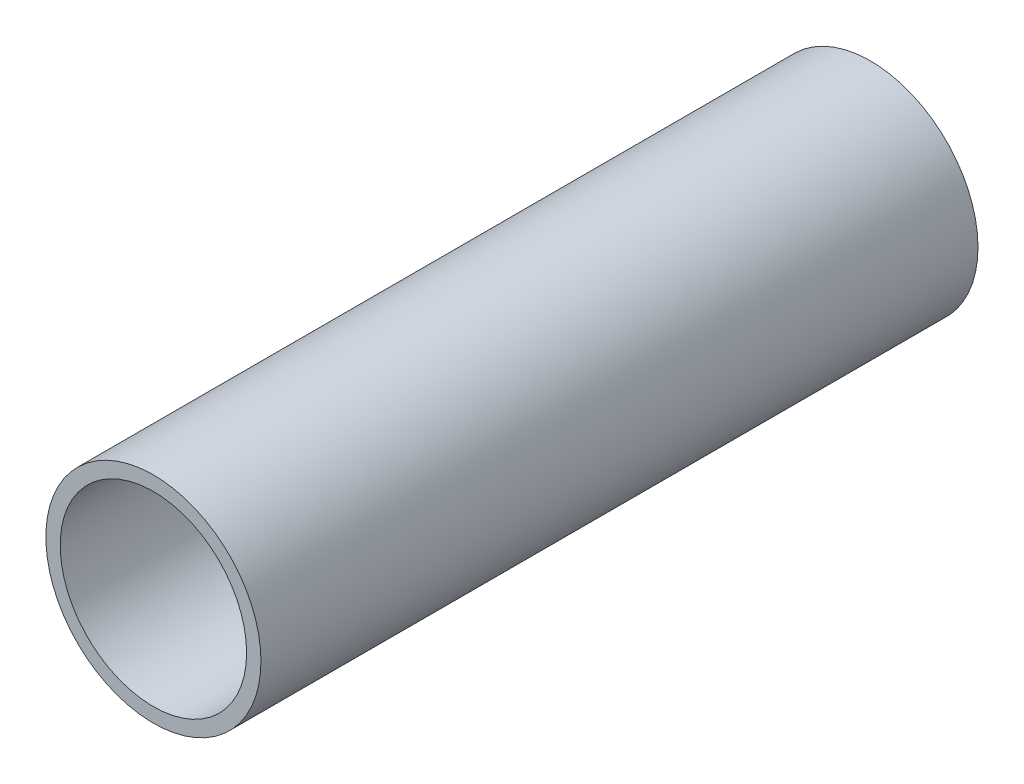
SolidWorks part; units mm, degrees
ref_plane "정면" through (0, 0, 0) normal (0, 0, 1) x (1, 0, 0)
ref_plane "윗면" through (0, 0, 0) normal (0, 1, 0) x (1, 0, 0)
ref_plane "우측면" through (0, 0, 0) normal (1, 0, 0) x (0, 0, -1)
sketch "스케치1" plane through (0, 0, 0) normal (0, 0, 1) x (1, 0, 0)
  circle A0 centre (0, 0) radius 22.5
  circle A1 centre (0, 0) radius 19.5
  dimension "D1" = 45
  dimension "D2" = 39
extrude "보스-돌출1" add sketch "스케치1" along normal blind 150
